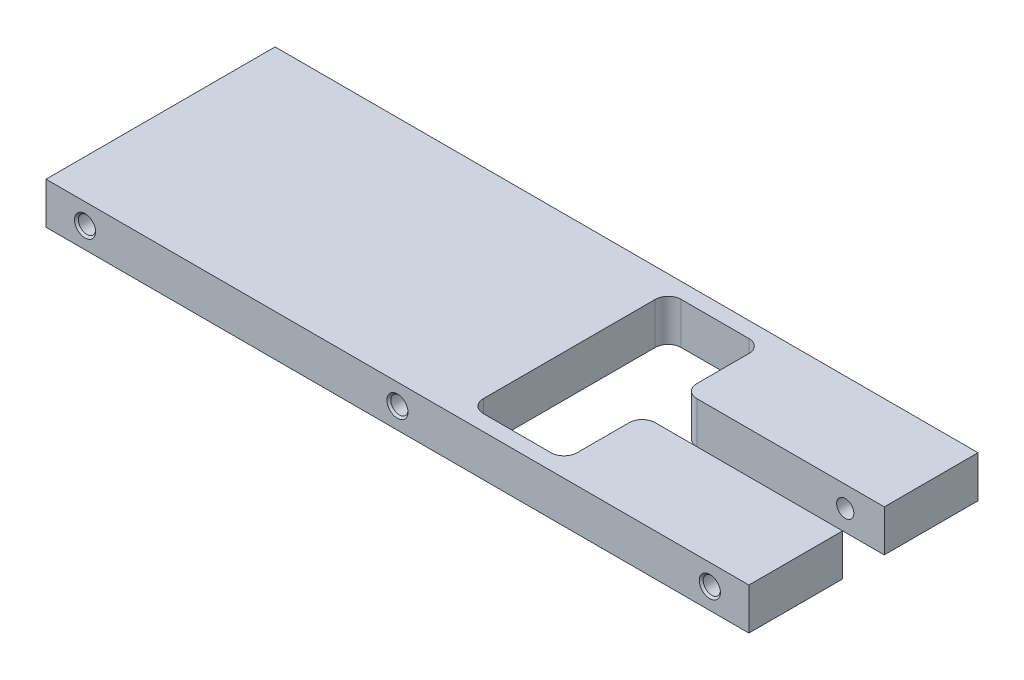
SolidWorks part; units mm, degrees
ref_plane "Front Plane" through (0, 0, 0) normal (0, 0, 1) x (1, 0, 0)
ref_plane "Top Plane" through (0, 0, 0) normal (0, 1, 0) x (1, 0, 0)
ref_plane "Right Plane" through (0, 0, 0) normal (1, 0, 0) x (0, 0, -1)
sketch "Sketch1" plane through (0, 0, 0) normal (0, 1, 0) x (1, 0, 0)
  line L0 (-88.7836, 0) -> (129.8578, 0) construction
  line L1 (0, -68.0095) -> (0, 72.1169) construction
  line L2 (14, 76.7773) -> (14, -75.8673) construction
  line L3 (-53.5, 36) -> (81.5, 36)
  line L4 (-53.5, 36) -> (-53.5, -8)
  line L5 (-53.5, -8) -> (81.5, -8)
  line L6 (81.5, 36) -> (81.5, -8)
  line L7 (-90.9953, 14) -> (129.8578, 14) construction
  dimension "D1" = 135
  dimension "D2" = 44
  dimension "D3" = 67.5
  dimension "D4" = 14
  dimension "D5" = 22
  dimension "D6" = 14
extrude "Boss-Extrude1" add sketch "Sketch1" along normal blind 8 contours L3 L6 L5 L4
sketch "Sketch2" plane through (0, 0, 8) normal (0, 0, 1) x (1, 0, 0)
  line L0 (-57.7018, 4) -> (90.0897, 4) construction
  line L1 (0, 14.2518) -> (0, -9.682) construction
  line L2 (-57.7018, 0) -> (89.2919, 0) construction
  point P7 (-46, 4)
  point P9 (14, 4)
  point P15 (74, 4)
  dimension "D1" = 4
  dimension "D4" = 60
  dimension "D2" = 14
  dimension "D3" = 3
sketch "Sketch7" plane through (0, 0, 0) normal (0, 1, 0) x (1, 0, 0)
  line L0 (0, -12.9754) -> (0, 42.571) construction
  line L1 (-15.8176, 0) -> (64.7597, 0) construction
  line L2 (-13.3278, 14) -> (93.3772, 14) construction
  line L3 (81.5, 10) -> (81.5, 18)
  line L4 (81.5, 18) -> (43, 18)
  line L5 (81.5, 10) -> (43, 10)
  line L6 (14, 41.4416) -> (14, -13.8806) construction
  line L7 (34, 7.2691) -> (34, 21.2402) construction
  line L8 (43, 10) -> (43, -5)
  line L9 (25, 33) -> (43, 33)
  line L10 (25, 33) -> (25, -5)
  line L11 (25, -5) -> (43, -5)
  line L12 (43, 33) -> (43, 18)
  dimension "D4" = 14
  dimension "D1" = 8
  dimension "D3" = 4
  dimension "D5" = 14
  dimension "D7" = 67.5
  dimension "D6" = 34
  dimension "D2" = 38
  dimension "D8" = 19
  dimension "D9" = 18
  dimension "D10" = 9
extrude "Cut-Extrude1" cut sketch "Sketch7" along normal blind 10 contours L5 L8 L11 L10 L9 L12 L4 L3
fillet "Fillet1" radius 2.5 4 edges at (43, 4, 5) (25, 4, 5) (25, 4, -33) (43, 4, -33)
fillet "Fillet2" radius 2.5 2 edges at (43, 4, -10) (43, 4, -18)
hole_wizard "M4x0.7 Tapped Hole1" positions "Sketch8" profile "Sketch9" tap size "M4x0.7" standard "ANSI Metric" end condition through all
sketch "Sketch8" plane through (0, 0, 8) normal (0, 0, 1) x (1, 0, 0)
  point P0 (-46, 4)
  point P3 (14, 4)
  point P6 (74, 4)
sketch "Sketch9" plane through (-46, 4, 8) normal (1, 0, 0) x (0, -1, 0)
  line L0 (0, 0) -> (0, 44)
  line L1 (0, 44) -> (1.65, 44)
  line L2 (1.65, 44) -> (1.65, 0.375)
  line L3 (1.65, 0.375) -> (2.025, 0)
  line L5 (2.025, 0) -> (0, 0)
  line L6 (-1.65, 0.375) -> (-2.025, 0) construction
  line L11 (0, -6.35) -> (0, 107.95) construction
  dimension "Thru Tap Drill Dia." = 3.3
  dimension "Thru Tap Drill Depth" = 44
  dimension "Near C'Sink Dia." = 4.05
  dimension "Near C'Sink Angle" = 90
cosmetic thread "Hole Thread1"
cosmetic thread "Hole Thread2"
cosmetic thread "Hole Thread3"
equation "\"plateC_length\"=135"
equation "\"D1@Sketch1\"=\"plateC_length\""
equation "\"plateC_width\"=44"
equation "\"D2@Sketch1\"=\"plateC_width\""
equation "\"D3@Sketch1\"=\"plateC_length\"/2"
equation "\"plateC_offsetX\"=14"
equation "\"D4@Sketch1\"=\"plateC_offsetX\""
equation "\"D5@Sketch1\"=\"plateC_width\"/2"
equation "\"plateC_offsetZ\"=14"
equation "\"D6@Sketch1\"=\"plateC_offsetZ\""
equation "\"plateC_thickness\"= 8"
equation "\"D1@Boss-Extrude1\"=\"plateC_thickness\""
equation "\"D1@Sketch2\"=\"plateC_thickness\"/2"
equation "\"D5@Sketch7\"=\"plateC_offsetX\""
equation "\"D7@Sketch7\"=\"plateC_length\"/2"
equation "\"D4@Sketch7\"=\"plateC_offsetZ\""
equation "\"plateC_opening_idA\"=14"
equation "\"plateC_opening_posX\"= 34"
equation "\"D6@Sketch7\"=\"plateC_opening_posX\""
equation "\"plateC_opening_width\"= 38"
equation "\"D2@Sketch7\"=\"plateC_opening_width\""
equation "\"D8@Sketch7\"=\"plateC_opening_width\"/2"
equation "\"plateC_opening_length\"= 18"
equation "\"D9@Sketch7\"=\"plateC_opening_length\""
equation "\"D10@Sketch7\"=\"plateC_opening_length\"/2"
equation "\"D2@Sketch2\"=\"plateC_offsetX\""
equation "\"plateC_bolt_spacingX\"=60"
equation "\"D4@Sketch2\"=\"plateC_bolt_spacingX\""
